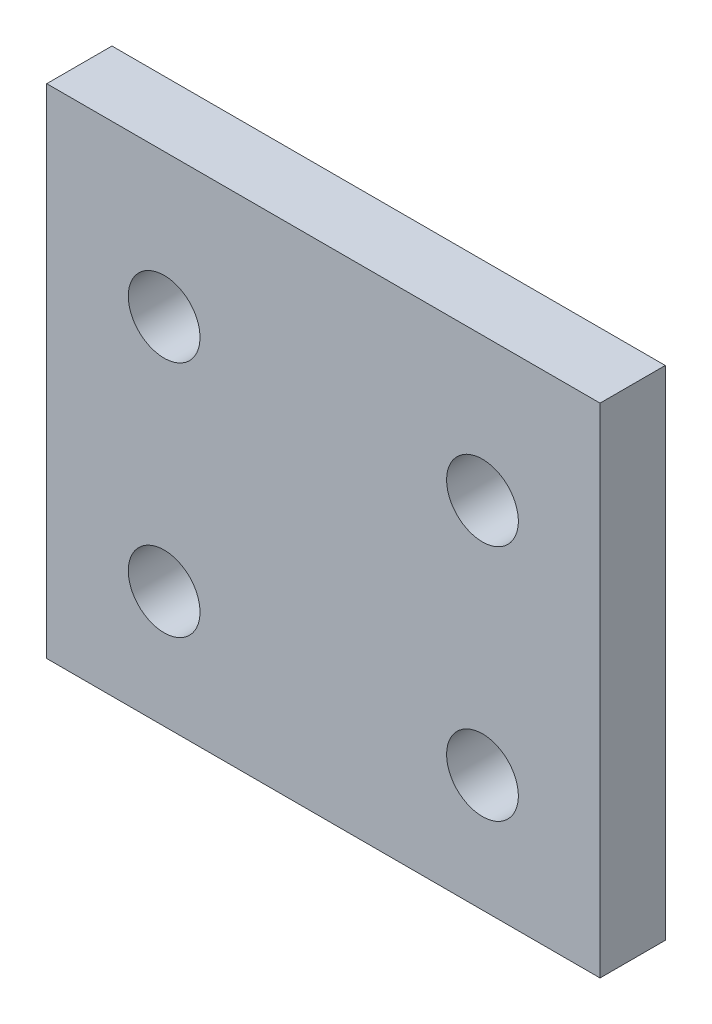
SolidWorks part; units mm, degrees
ref_plane "Front" through (0, 0, 0) normal (0, 0, 1) x (1, 0, 0)
ref_plane "Top" through (0, 0, 0) normal (0, 1, 0) x (1, 0, 0)
ref_plane "Right" through (0, 0, 0) normal (1, 0, 0) x (0, 0, -1)
sketch "Sketch1" plane through (0, 0, 0) normal (0, 0, 1) x (1, 0, 0)
  line L1 (0, 0) -> (21.2113, 0)
  line L2 (0, 0) -> (0, 19.086)
  line L3 (0, 19.086) -> (21.2113, 19.086)
  line L4 (21.2113, 0) -> (21.2113, 19.086)
  dimension "D1" = 19.086
  dimension "D2" = 21.2113
extrude "Boss-Extrude1" add sketch "Sketch1" along normal blind 2.5
sketch "Sketch2" plane through (0, 0, 0) normal (0, 0, -1) x (-1, 0, 0)
  line L0 (-21.2113, 19.086) -> (0, 19.086) construction
  line L1 (-21.2113, 0) -> (-21.2113, 19.086) construction
  circle A0 centre (-16.7032, 13.5977) radius 1.375
  circle A1 centre (-4.5006, 13.5977) radius 1.375
  circle A2 centre (-16.7032, 4.4801) radius 1.375
  circle A3 centre (-4.5006, 4.4801) radius 1.375
  point P8 (-16.4992, 5.9938)
  point P9 (-15.054, 13.2658)
  dimension "D1" = 2.75
  dimension "D2" = 12.2026
  dimension "D3" = 9.1176
  dimension "D4" = 5.4883
  dimension "D5" = 4.5081
extrude "Cut-Extrude1" cut sketch "Sketch2" against normal through all
